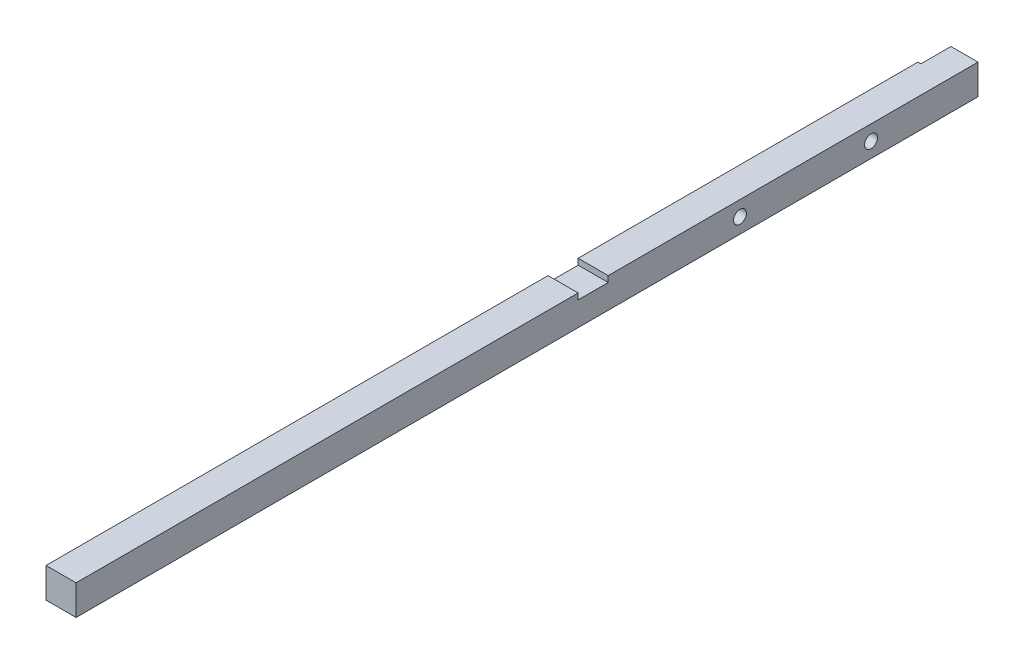
SolidWorks part; units mm, degrees
ref_plane "Plan de face" through (0, 0, 0) normal (0, 0, 1) x (1, 0, 0)
ref_plane "Plan de dessus" through (0, 0, 0) normal (0, 1, 0) x (1, 0, 0)
ref_plane "Plan de droite" through (0, 0, 0) normal (1, 0, 0) x (0, 0, -1)
sketch "Esquisse1" plane through (0, 0, 0) normal (0, 0, 1) x (1, 0, 0)
  line L0 (-5, 5) -> (5, -5) construction
  line L1 (-5, 5) -> (5, 5)
  line L2 (-5, 5) -> (-5, -5)
  line L3 (-5, -5) -> (5, -5)
  line L4 (5, 5) -> (5, -5)
  dimension "D1" = 10
extrude "Boss.-Extru.1" add sketch "Esquisse1" along normal offset from surface (300 mm away) 2 from vertex at 7
sketch "Esquisse4" plane through (5, 0, 0) normal (1, 0, 0) x (0, 0, -1)
  line L0 (-140, 184.2) -> (-140, 3) construction
  line L1 (-140, 5) -> (-130, 5)
  line L2 (-140, 5) -> (-140, 3)
  line L3 (-140, 3) -> (-130, 3)
  line L4 (-130, 5) -> (-130, 3)
  line L5 (-130, 184.2) -> (-130, 3) construction
  line L6 (-307, 5) -> (-7, 5) construction
  dimension "D1" = 2
extrude "Enlèv. mat.-Extru.3" cut sketch "Esquisse4" against normal through all
sketch "Esquisse5" plane through (5, 0, 0) normal (1, 0, 0) x (0, 0, -1)
  line L0 (-307, -5) -> (-7, -5) construction
  line L1 (-130, -5) -> (-140, -5)
  line L2 (-130, -5) -> (-130, -3)
  line L3 (-130, -3) -> (-140, -3)
  line L4 (-140, -5) -> (-140, -3)
  line L7 (-140, 3) -> (-140, 184.2) construction
  line L8 (-130, 3) -> (-130, 184.2) construction
  dimension "D1" = 2
extrude "Enlèv. mat.-Extru.4" [suppressed] cut sketch "Esquisse5" against normal through all
sketch "Esquisse6" plane through (-5, 0, 0) normal (-1, 0, 0) x (0, 0, 1)
  line L1 (7, -5) -> (17, -5)
  line L2 (7, -5) -> (7, 5)
  line L3 (7, 5) -> (17, 5)
  line L4 (17, -5) -> (17, 5)
extrude "Enlèv. mat.-Extru.5" cut sketch "Esquisse6" against normal blind 1
hole_wizard "Dégagement M41" positions "Esquisse8" profile "Esquisse9" hole size "M4" standard "Ansi Metric" end condition through all
sketch "Esquisse8" plane through (-5, 0, 0) normal (-1, 0, 0) x (0, 0, 1)
  point P0 (86.1865, 0)
  point P5 (42.5865, 0)
sketch "Esquisse9" plane through (-5, 0, 86.1865) normal (0, 1, 0) x (0, 0, 1)
  line L0 (0, 0) -> (0, 10)
  line L1 (0, 10) -> (2.15, 10)
  line L2 (2.15, 10) -> (2.15, 0)
  line L5 (2.15, 0) -> (0, 0)
  line L11 (0, -6.35) -> (0, 107.95) construction
  dimension "Diamètre du perçage jusqu'au prochain" = 4.3
  dimension "Profondeur du perçage jusqu'au prochain" = 10
